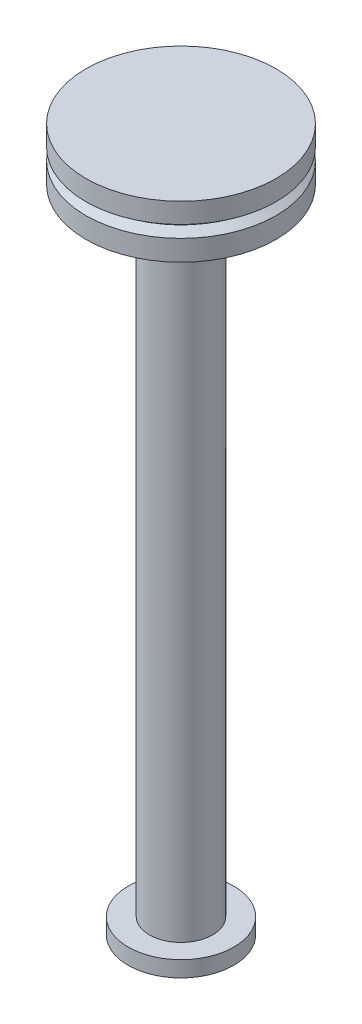
SolidWorks part; units mm, degrees
ref_plane "Alzado" through (0, 0, 0) normal (0, 0, 1) x (1, 0, 0)
ref_plane "Planta" through (0, 0, 0) normal (0, 1, 0) x (1, 0, 0)
ref_plane "Vista lateral" through (0, 0, 0) normal (1, 0, 0) x (0, 0, -1)
sketch "Sketch1" plane through (0, 0, 0) normal (0, 0, 1) x (1, 0, 0)
  line L0 (0, 0) -> (0, 130)
  line L1 (0, 130) -> (6, 130)
  line L4 (6, 122.5254) -> (6, 0)
  line L5 (6, 0) -> (0, 0)
  line L6 (6, 122.5254) -> (6, 130)
  dimension "D1" = 130
  dimension "D2" = 6
revolve "Revolve1" add sketch "Sketch1" angle 360 about L0
sketch "Sketch2" plane through (0, 0, 0) normal (0, 0, 1) x (1, 0, 0)
  line L0 (0, 130) -> (18, 130)
  line L1 (6, 130) -> (-6, 130) construction
  line L2 (18, 130) -> (18, 126.1858)
  line L3 (0, 130) -> (0, 120)
  line L5 (18, 126.1858) -> (16.4184, 125)
  line L6 (16.4184, 125) -> (18, 123.9137)
  line L7 (18, 123.9137) -> (18, 120)
  line L10 (0, 120) -> (18, 120)
revolve "Revolve2" add sketch "Sketch2" angle 360 about L3
sketch "Sketch3" plane through (0, 0, 0) normal (0, -1, 0) x (1, 0, 0)
  circle A0 centre (0, 0) radius 10
extrude "Boss-Extrude1" add sketch "Sketch3" along normal blind 3
